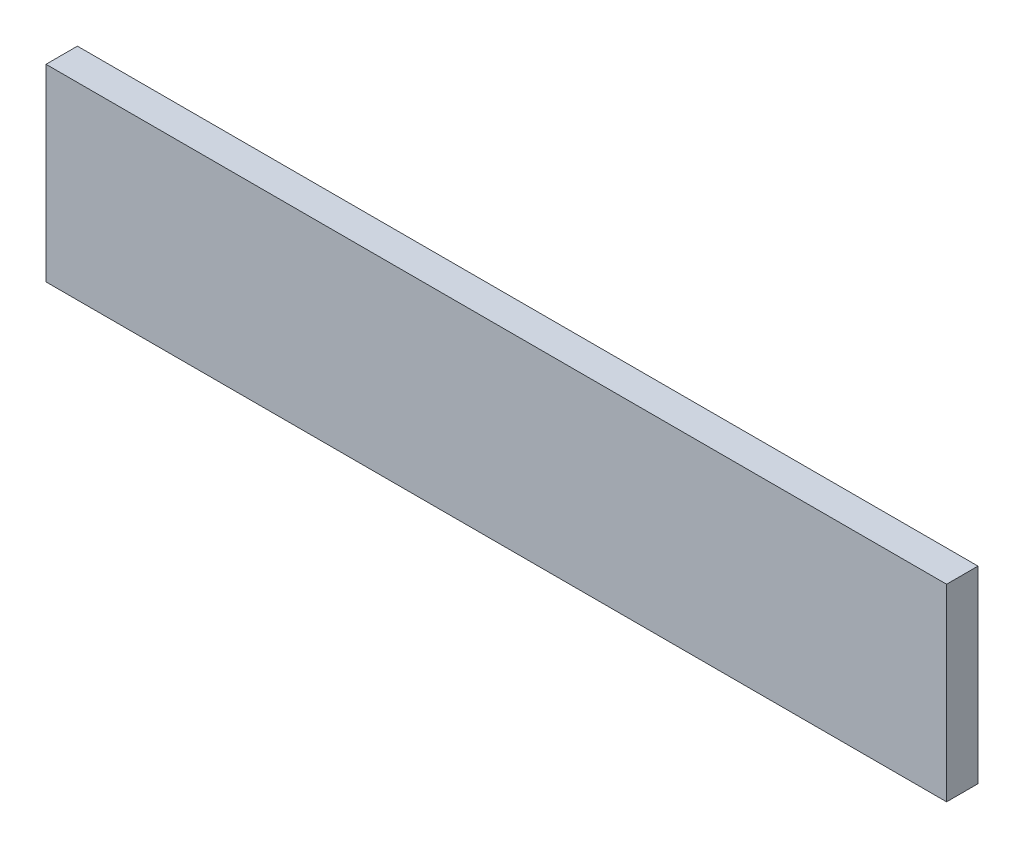
SolidWorks part; units mm, degrees
material "1060 Alloy"
ref_plane "Front Plane" through (0, 0, 0) normal (0, 0, 1) x (1, 0, 0)
ref_plane "Top Plane" through (0, 0, 0) normal (0, 1, 0) x (1, 0, 0)
ref_plane "Right Plane" through (0, 0, 0) normal (1, 0, 0) x (0, 0, -1)
sketch "Sketch1" plane through (0, 0, 0) normal (0, 0, 1) x (1, 0, 0)
  line L1 (-43, -9) -> (43, -9)
  line L2 (-43, -9) -> (-43, 9)
  line L3 (-43, 9) -> (43, 9)
  line L4 (43, -9) -> (43, 9)
  line L5 (-43, -9) -> (43, 9) construction
  line L6 (-43, 9) -> (43, -9) construction
  point P0 (0, 0)
  dimension "D1" = 86
  dimension "D2" = 18
extrude "Boss-Extrude1" add sketch "Sketch1" along normal blind 3
